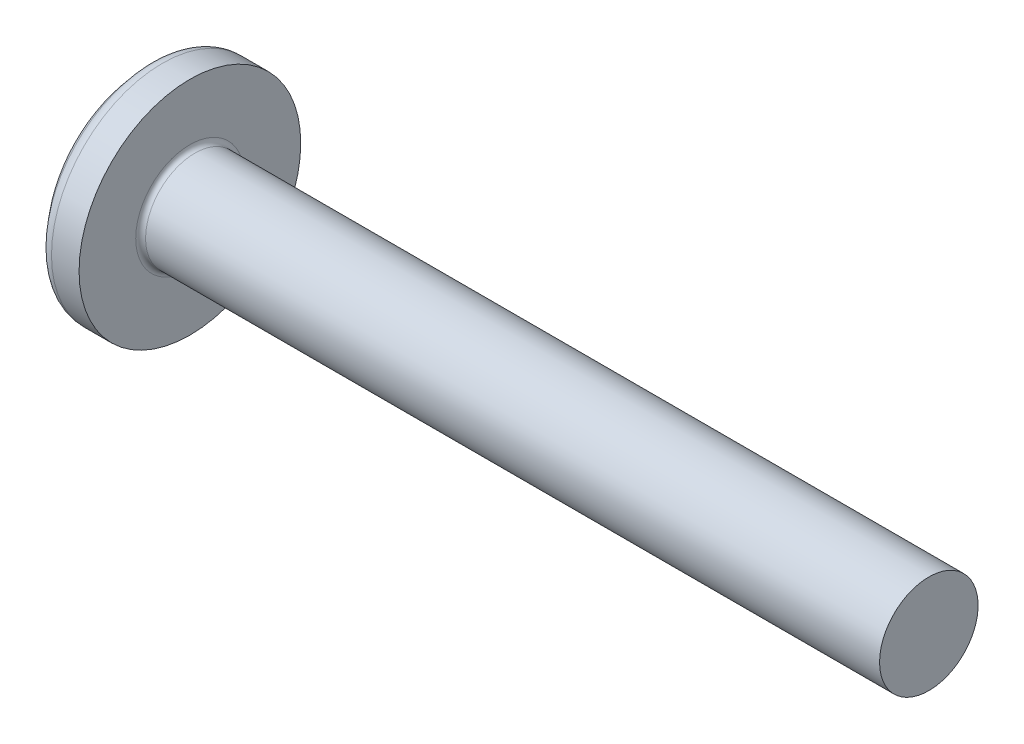
SolidWorks part; units mm, degrees
material "普通碳钢"
ref_plane "Plane1" through (0, 0, 0) normal (0, 0, 1) x (1, 0, 0)
ref_plane "Plane2" through (0, 0, 0) normal (0, 1, 0) x (1, 0, 0)
ref_plane "Plane3" through (0, 0, 0) normal (1, 0, 0) x (0, 0, -1)
sketch "BodySke" plane through (0, 0, 0) normal (0, 0, 1) x (1, 0, 0)
  line L0 (1.6, 1) -> (1.6, 2.25)
  line L2 (-25.4, 0) -> (127, 0) construction
  line L3 (16.6, 0) -> (0, 0)
  line L4 (1.6, 1) -> (16.6, 1)
  line L5 (16.6, 1) -> (16.6, 0)
  line L6 (1.0403, 2.25) -> (1.6, 2.25)
  arc A0 (0.8412, 2.1625) -> (0, 0) centre (3.2, 0) ccw
  arc A2 (0.8412, 2.1625) -> (1.0403, 2.25) centre (1.0403, 1.98) cw
  dimension "Head_fillet_rad" = 0.27
  dimension "Head_crown_rad" = 3.2
  dimension "D1" = 15
  dimension "Head_ht" = 1.6
  dimension "Diameter" = 2
  dimension "Head_dia" = 4.5
revolve "Base-Revolve" add sketch "BodySke"
cosmetic thread "ThreadCosmetic" [suppressed]
fillet "Fillet1" radius 0.1 1 edges at (1.6, 0, 1)
sketch "Sketch3" plane through (0, 0, 0) normal (1, 0, 0) x (0, 0, -1)
  line L0 (0.37, -0.95) -> (-0.37, -0.95)
  line L1 (0.37, -0.95) -> (0.37, 0.95)
  line L2 (-0.37, 0.95) -> (0.37, 0.95)
  line L3 (-0.37, 0.95) -> (-0.37, -0.95)
  dimension "D1" = 0.95
  dimension "Cross_dia" = 1.9
  dimension "D2" = 0.37
  dimension "Cross_width" = 0.74
ref_plane "Plane4" through (1.75, 0, 0) normal (1, 0, 0) x (0, 0, -1)
sketch "Sketch4" plane through (1.75, 0, 0) normal (1, 0, 0) x (0, 0, -1)
  line L0 (0.37, -0.5275) -> (-0.37, -0.5275)
  line L1 (0.37, -0.5275) -> (0.37, 0.5275)
  line L2 (-0.37, 0.5275) -> (0.37, 0.5275)
  line L3 (-0.37, 0.5275) -> (-0.37, -0.5275)
  dimension "D1" = 0.74
  dimension "D2" = 1.055
  dimension "D3" = 0.37
  dimension "D4" = 0.5275
loft "Recess" cut profiles "Sketch3", "Sketch4"
pattern_circular "RecPat" count 2 every 90 about axis through (0, 0, 0) along (1, 0, 0) of "Recess"
sketch "RecCorSke" plane through (0, 0, 0) normal (0, 0, 1) x (1, 0, 0)
  line L0 (-3.175, 0) -> (15.875, 0) construction
  line L1 (-25.4, 0) -> (127, 0) construction
  line L2 (0, 0) -> (0, 0.6784)
  line L3 (0, 0.6784) -> (1.75, 0.556)
  line L4 (1.75, 0.556) -> (1.9307, 0)
  line L5 (1.9307, 0) -> (0, 0)
  dimension "Diameter" = 1.112
  dimension "Depth" = 1.75
  dimension "Draft_angle" = 4
  dimension "Bottom_angle" = 18
revolve "RecessCore" cut sketch "RecCorSke" angle 360 about L0
